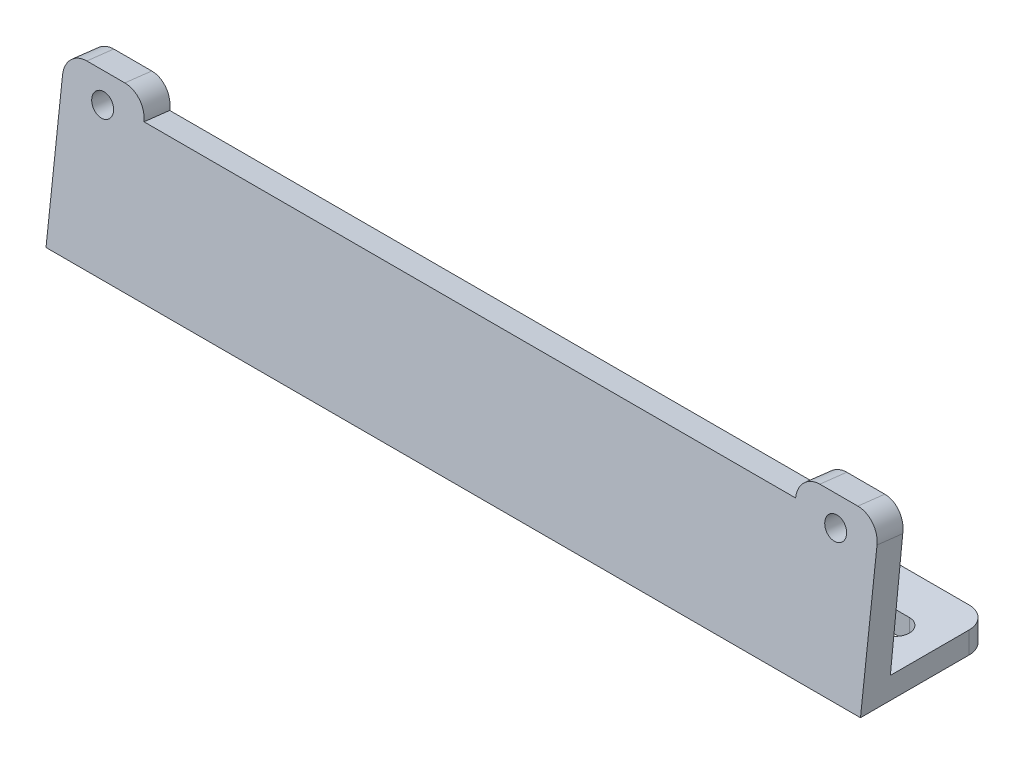
SolidWorks part; units mm, degrees
ref_plane "Front Plane" through (0, 0, 0) normal (0, 0, 1) x (1, 0, 0)
ref_plane "Top Plane" through (0, 0, 0) normal (0, 1, 0) x (1, 0, 0)
ref_plane "Right Plane" through (0, 0, 0) normal (1, 0, 0) x (0, 0, -1)
sketch "Sketch1" plane through (0, 0, 0) normal (0, 1, 0) x (1, 0, 0)
  line L0 (-67.5, 0) -> (-62.5, 0) construction
  line L1 (-75, 10) -> (75, 10)
  line L2 (-75, 10) -> (-75, -10)
  line L3 (-75, -10) -> (75, -10)
  line L4 (75, 10) -> (75, -10)
  line L5 (-75, 10) -> (75, -10) construction
  line L6 (-75, -10) -> (75, 10) construction
  line L7 (-67.5, 2.5) -> (-62.5, 2.5)
  line L8 (-67.5, -2.5) -> (-62.5, -2.5)
  line L9 (62.5, 0) -> (67.5, 0) construction
  line L10 (62.5, 2.5) -> (67.5, 2.5)
  line L11 (62.5, -2.5) -> (67.5, -2.5)
  arc A0 (-67.5, 2.5) -> (-67.5, -2.5) centre (-67.5, 0) ccw
  arc A1 (-62.5, -2.5) -> (-62.5, 2.5) centre (-62.5, 0) ccw
  arc A2 (62.5, 2.5) -> (62.5, -2.5) centre (62.5, 0) ccw
  arc A3 (67.5, -2.5) -> (67.5, 2.5) centre (67.5, 0) ccw
  point P0 (0, 0)
  point P8 (-65, 0)
  point P13 (65, 0)
  dimension "D3" = 2.5
  dimension "D4" = 2.5
  dimension "D1" = 150
  dimension "20" = 20
  dimension "D5" = 5
  dimension "D6" = 5
  dimension "D7" = 130
  dimension "D8" = 65
extrude "Boss-Extrude1" add sketch "Sketch1" along normal blind 4
sketch "Sketch3" plane through (75, 0, 0) normal (1, 0, 0) x (0, 0, -1)
  line L0 (-10, 0) -> (-14, 0)
  line L1 (-14, 0) -> (-10.4841, 30)
  line L2 (-10.4841, 30) -> (-5.5181, 29.418)
  line L3 (-5.5181, 29.418) -> (-10, 4)
  line L4 (-10, 4) -> (-10, 0)
  line L5 (-10, 4) -> (10, 4) construction
  dimension "D1" = 5
  dimension "D2" = 4
  dimension "D3" = 30
  dimension "D4" = 80
extrude "Boss-Extrude3" add sketch "Sketch3" against normal up to surface (150 mm away) up to face at (-75, 2, 0)
fillet "Fillet1" radius 4 2 edges at (-75, 29.709, 8.0011) (75, 29.709, 8.0011)
sketch "Sketch4" plane through (0, 1.6185, 13.8103) normal (0, 0.1164, 0.9932) x (1, 0, 0)
  line L0 (-71, 28.5757) -> (71, 28.5757) construction
  line L1 (-60, 28.5757) -> (60, 28.5757)
  line L2 (-60, 28.5757) -> (-60, 3.3704)
  line L3 (-60, 3.3704) -> (60, 3.3704)
  line L4 (60, 28.5757) -> (60, 3.3704)
  line L5 (-75, -1.6296) -> (75, -1.6296) construction
  line L6 (-75, -1.6296) -> (-75, 24.5757) construction
  line L7 (75, 24.5757) -> (75, -1.6296) construction
  dimension "D1" = 5
  dimension "D2" = 15
  dimension "D3" = 15
extrude "Cut-Extrude1" cut sketch "Sketch4" against normal blind 10
fillet "Fillet2" radius 4 2 edges at (-60, 29.709, 8.0011) (60, 29.709, 8.0011)
fillet "Fillet3" radius 4 2 edges at (-75, 2, -10) (75, 2, -10)
sketch "Sketch6" plane through (0, 4, 0) normal (0, 1, 0) x (1, 0, 0)
  line L1 (-60, -3.4628) -> (64, -3.4628)
  line L2 (-60, -3.4628) -> (-60, -10.4841)
  line L3 (-60, -10.4841) -> (64, -10.4841)
  line L4 (64, -3.4628) -> (64, -10.4841)
extrude "Boss-Extrude4" add sketch "Sketch6" against normal up to surface (4 mm away) up to face at (-65, 0, 0)
sketch "Sketch8" plane through (75, 0, 0) normal (1, 0, 0) x (0, 0, -1)
  line L0 (-6.2139, 25.4722) -> (-8.497, 4)
  line L1 (-10, 4) -> (6, 4) construction
  line L2 (-10.9497, 26.0272) -> (-14, 0) construction
  line L3 (-8.497, 4) -> (-13.5312, 4)
  line L4 (-13.5312, 4) -> (-10.9497, 26.0272)
  line L5 (-10.9497, 26.0272) -> (-6.2139, 25.4722)
  dimension "D1" = 5
extrude "Boss-Extrude5" add sketch "Sketch8" against normal up to surface (150 mm away)
sketch "Sketch5" plane through (0, 1.6185, 13.8103) normal (0, 0.1164, 0.9932) x (1, 0, 0)
  line L0 (-71, 28.5757) -> (-64, 28.5757) construction
  line L1 (75, 24.5757) -> (75, -1.6296) construction
  line L3 (64, 28.5757) -> (71, 28.5757) construction
  line L4 (-75, -1.6296) -> (-75, 24.5757) construction
  circle A0 centre (-67.5, 23.5757) radius 2.005
  circle A1 centre (67.5, 23.5757) radius 2.005
  dimension "D3" = 4.01
  dimension "D4" = 4.01
  dimension "D1" = 5
  dimension "D2" = 7.5
  dimension "D5" = 7.5
  dimension "D6" = 5
extrude "Cut-Extrude2" cut sketch "Sketch5" against normal blind 10
